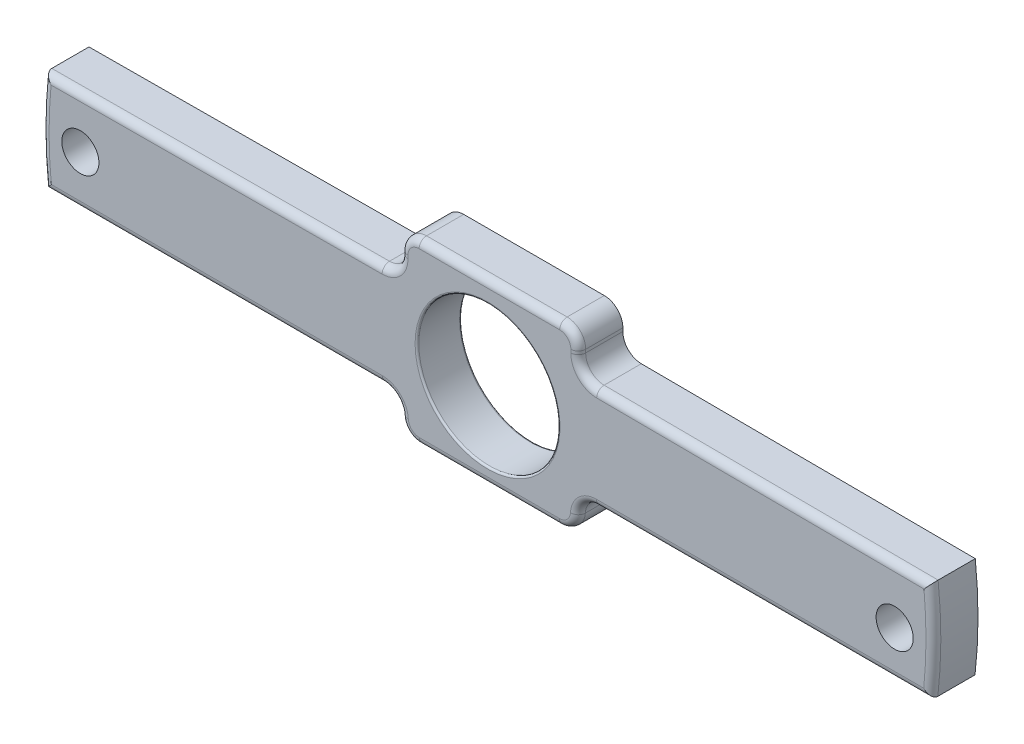
SolidWorks part; units mm, degrees
material "Plastique personnalisé"
ref_plane "Plan de face" through (0, 0, 0) normal (0, 0, 1) x (1, 0, 0)
ref_plane "Plan de dessus" through (0, 0, 0) normal (0, 1, 0) x (1, 0, 0)
ref_plane "Plan de droite" through (0, 0, 0) normal (1, 0, 0) x (0, 0, -1)
sketch "Esquisse1" plane through (0, 0, 0) normal (0, 0, 1) x (1, 0, 0)
  line L1 (-105.7654, -12) -> (94.2346, -12)
  line L2 (-105.7654, -12) -> (-105.7654, 12)
  line L3 (-105.7654, 12) -> (94.2346, 12)
  line L4 (94.2346, -12) -> (94.2346, 12)
  line L5 (-105.7654, -12) -> (94.2346, 12) construction
  line L6 (-105.7654, 12) -> (94.2346, -12) construction
  point P1 (-5.7654, 0)
  dimension "D1" = 24
  dimension "D2" = 200
extrude "Boss.-Extru.1" add sketch "Esquisse1" along normal blind 6
sketch "Esquisse2" plane through (0, 0, 6) normal (0, 0, 1) x (1, 0, 0)
  line L0 (-5.7654, -12) -> (-5.7654, 24.5416) construction
  line L1 (-105.7654, -12) -> (94.2346, -12) construction
  line L2 (113.5551, 0) -> (-125.5876, -0.6472) construction
sketch "Esquisse3" plane through (0, 0, 6) normal (0, 0, 1) x (1, 0, 0)
  circle A0 centre (-6.0163, -0.3236) radius 9.5
extrude "Enlèv. mat.-Extru.1" cut sketch "Esquisse3" against normal blind 6
sketch "Esquisse4" plane through (0, 0, 6) normal (0, 0, 1) x (1, 0, 0)
  circle A0 centre (-6.0163, -0.3236) radius 60
  circle A1 centre (-6.0163, -0.3236) radius 114.2751
extrude "Enlèv. mat.-Extru.2" cut sketch "Esquisse4" against normal blind 6
sketch "Esquisse5" plane through (0, 0, 6) normal (0, 0, 1) x (1, 0, 0)
  line L5 (-82.1035, -0.5295) -> (-18.5218, -0.3574) construction
  line L6 (-5.7654, 21.2618) -> (-5.7654, -21.2211) construction
  line L7 (-69.8032, 21.8171) -> (-17.7922, 22.0986)
  line L8 (-69.6824, -7.2681) -> (-17.6707, -7.2681)
  line L9 (-69.6824, -7.2681) -> (-69.6824, -22.8093)
  line L10 (-69.6824, -22.8093) -> (-17.6707, -22.8093)
  line L11 (-17.6707, -7.2681) -> (-17.6707, -22.8093)
  line L12 (-17.7081, 6.5577) -> (-17.7922, 22.0986)
  line L13 (-69.7191, 6.2762) -> (-17.7081, 6.5577)
  line L14 (-69.7191, 6.2762) -> (-69.8032, 21.8171)
  line L15 (58.1516, -7.2681) -> (58.1516, -22.8093)
  line L16 (58.1516, -22.8093) -> (6.1399, -22.8093)
  line L17 (6.1399, -7.2681) -> (6.1399, -22.8093)
  line L18 (58.1516, -7.2681) -> (6.1399, -7.2681)
  line L19 (58.1883, 6.2762) -> (58.2724, 21.8171)
  line L20 (58.2724, 21.8171) -> (6.2614, 22.0986)
  line L21 (6.1773, 6.5577) -> (6.2614, 22.0986)
  line L22 (58.1883, 6.2762) -> (6.1773, 6.5577)
extrude "Enlèv. mat.-Extru.3" cut sketch "Esquisse5" against normal blind 6
fillet "Congé1" radius 2.5 4 edges at (6.1773, 6.5577, 3) (6.1399, -7.2681, 3) (-17.6707, -7.2681, 3) (-17.7081, 6.5577, 3)
fillet "Congé2" radius 2.5 4 edges at (6.2068, 12, 3) (-17.7376, 12, 3) (-17.6707, -12, 3) (6.1399, -12, 3)
fillet "Congé3" radius 1 18 edges at (-42.8919, -7.2681, 6) (31.1102, -7.2681, 6) (6.9202, -7.9536, 6) (5.3668, -11.3145, 6) (-5.7654, -12, 6) (-16.8976, -11.3145, 6) (31.1471, 6.4226, 6) (6.9135, 7.286, 6) (6.192, 9.2721, 6) (5.4658, 11.263, 6) (-5.7654, 12, 6) (-16.9965, 11.263, 6) (-17.7228, 9.2721, 6) (-42.9289, 6.4212, 6) (53.9835, -0.4846, 6) (-66.0161, -0.486, 6) (-18.451, -7.9536, 6) (-18.4443, 7.286, 6)
fillet "Congé4" radius 0.25 1 edges at (3.4837, -0.3236, 6)
fillet "Congé5" radius 0.25 1 edges at (3.4837, -0.3236, 0)
sketch "Esquisse6" plane through (0, 0, 6) normal (0, 0, 1) x (1, 0, 0)
  circle A0 centre (48.7688, -1.1798) radius 2.5
  circle A1 centre (-60.8076, -0.5338) radius 2.5
extrude "Enlèv. mat.-Extru.4" cut sketch "Esquisse6" against normal through all
